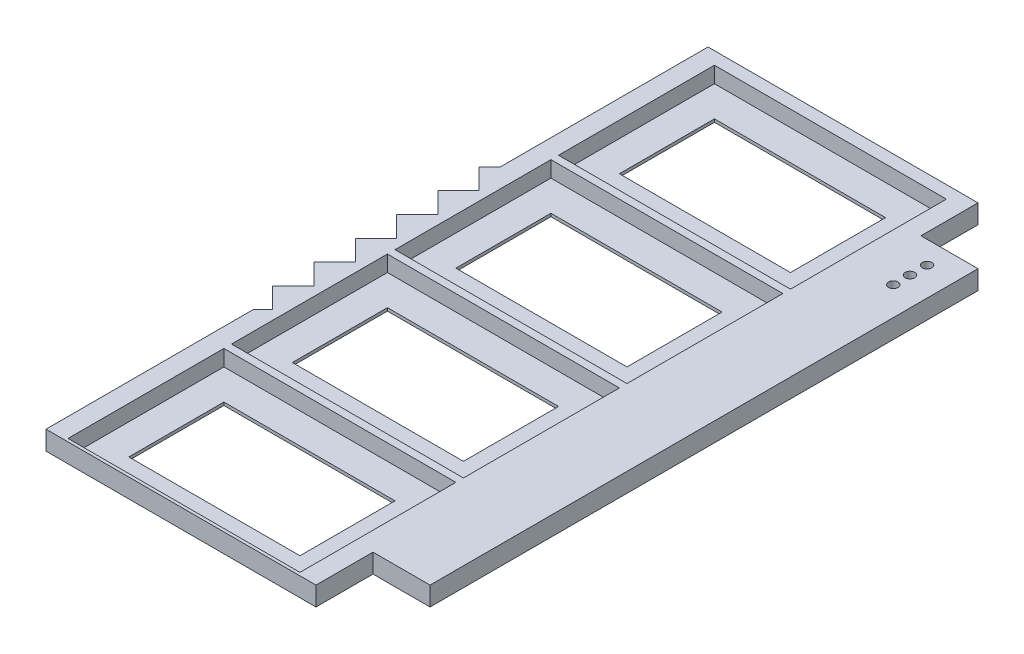
SolidWorks part; units mm, degrees
ref_plane "Front Plane" through (0, 0, 0) normal (0, 0, 1) x (1, 0, 0)
ref_plane "Top Plane" through (0, 0, 0) normal (0, 1, 0) x (1, 0, 0)
ref_plane "Right Plane" through (0, 0, 0) normal (1, 0, 0) x (0, 0, -1)
sketch "Sketch1" plane through (0, 0, 0) normal (0, 1, 0) x (1, 0, 0)
  line L0 (139.065, 94.1103) -> (139.065, -88.9) construction
  line L1 (-148.59, -107.95) -> (148.59, -107.95)
  line L2 (148.59, -107.95) -> (123.19, -107.95)
  line L3 (-156.21, 113.1603) -> (-137.0297, 113.1603)
  line L4 (148.59, -107.95) -> (148.59, 107.95)
  line L7 (148.59, -107.95) -> (-156.21, -107.95)
  line L8 (148.59, -107.95) -> (148.59, 113.1603)
  line L9 (148.59, 113.1603) -> (-156.21, 113.1603)
  line L10 (-156.21, -107.95) -> (-156.21, 113.1603)
  line L11 (-156.21, -107.95) -> (148.59, -107.95)
  line L12 (-156.21, -107.95) -> (-156.21, -106.95)
  line L13 (-156.21, -106.95) -> (148.59, -106.95)
  line L14 (148.59, -107.95) -> (148.59, -106.95)
  line L15 (148.59, -107.95) -> (148.59, 113.1603)
  line L16 (148.59, 113.1603) -> (123.19, 113.1603)
  line L17 (123.19, -107.95) -> (123.19, 113.1603)
  line L18 (123.19, -106.95) -> (45.72, -106.95)
  line L19 (123.19, -106.95) -> (123.19, -54.88)
  line L20 (123.19, -54.88) -> (45.72, -54.88)
  line L21 (45.72, -106.95) -> (45.72, -54.88)
  line L22 (123.19, -52.34) -> (45.72, -52.34)
  line L23 (123.19, -52.34) -> (123.19, -0.27)
  line L24 (123.19, -0.27) -> (45.72, -0.27)
  line L25 (45.72, -52.34) -> (45.72, -0.27)
  line L26 (123.19, 2.27) -> (45.72, 2.27)
  line L27 (123.19, 2.27) -> (123.19, 54.34)
  line L28 (123.19, 54.34) -> (45.72, 54.34)
  line L29 (45.72, 2.27) -> (45.72, 54.34)
  line L30 (123.19, 56.88) -> (45.72, 56.88)
  line L31 (123.19, 56.88) -> (123.19, 108.95)
  line L32 (123.19, 108.95) -> (45.72, 108.95)
  line L33 (45.72, 56.88) -> (45.72, 108.95)
  line L34 (33.02, -52.34) -> (-44.45, -52.34)
  line L35 (33.02, -106.95) -> (-44.45, -106.95)
  line L36 (33.02, -106.95) -> (33.02, -54.88)
  line L37 (33.02, -54.88) -> (-44.45, -54.88)
  line L38 (-44.45, -106.95) -> (-44.45, -54.88)
  line L39 (-57.15, -106.95) -> (-134.62, -106.95)
  line L40 (-57.15, -106.95) -> (-57.15, -54.88)
  line L41 (-57.15, -54.88) -> (-134.62, -54.88)
  line L42 (-134.62, -106.95) -> (-134.62, -54.88)
  line L43 (33.02, -52.34) -> (33.02, 0)
  line L44 (33.02, 0) -> (-44.45, 0)
  line L45 (-44.45, -52.34) -> (-44.45, 0)
  line L46 (-57.15, -52.34) -> (-134.62, -52.34)
  line L47 (-57.15, -52.34) -> (-57.15, -0.27)
  line L48 (-57.15, -0.27) -> (-134.62, -0.27)
  line L49 (-134.62, -52.34) -> (-134.62, -0.27)
  line L50 (33.02, 2.27) -> (-44.45, 2.27)
  line L51 (33.02, 2.27) -> (33.02, 54.34)
  line L52 (33.02, 54.34) -> (-44.45, 54.34)
  line L53 (-44.45, 2.27) -> (-44.45, 54.34)
  line L54 (-57.15, 2.27) -> (-134.62, 2.27)
  line L55 (-57.15, 2.27) -> (-57.15, 54.34)
  line L56 (-57.15, 54.34) -> (-134.62, 54.34)
  line L57 (-134.62, 2.27) -> (-134.62, 54.34)
  line L58 (33.02, 56.88) -> (-44.45, 56.88)
  line L59 (33.02, 56.88) -> (33.02, 108.95)
  line L60 (33.02, 108.95) -> (-44.45, 108.95)
  line L61 (-44.45, 56.88) -> (-44.45, 108.95)
  line L62 (-57.15, 56.88) -> (-134.62, 56.88)
  line L63 (-57.15, 56.88) -> (-57.15, 108.95)
  line L64 (-57.15, 108.95) -> (-134.62, 108.95)
  line L65 (-134.62, 56.88) -> (-134.62, 108.95)
  line L66 (-156.21, 113.1603) -> (-156.21, 100.4603)
  line L67 (-156.21, 113.1603) -> (-156.21, 93.98)
  line L68 (-156.21, 93.98) -> (-137.0297, 93.98)
  line L69 (-156.21, -107.95) -> (-137.16, -107.95)
  line L70 (-156.21, -107.95) -> (-156.21, -88.9)
  line L71 (-156.21, -88.9) -> (-137.16, -88.9)
  line L72 (-137.16, -107.95) -> (-137.16, -88.9)
  line L73 (-137.0297, 113.1603) -> (-137.0297, 93.98)
  line L74 (148.59, 113.1603) -> (129.54, 113.1603)
  line L75 (148.59, 113.1603) -> (148.59, 94.1103)
  line L76 (148.59, 94.1103) -> (129.54, 94.1103)
  line L77 (129.54, 113.1603) -> (129.54, 94.1103)
  line L78 (148.59, -107.95) -> (129.54, -107.95)
  line L79 (148.59, -107.95) -> (148.59, -88.9)
  line L80 (148.59, -88.9) -> (129.54, -88.9)
  line L81 (129.54, -107.95) -> (129.54, -88.9)
  circle A0 centre (139.065, 86.619) radius 1.5875
  circle A1 centre (139.065, 80.9106) radius 1.5875
  circle A2 centre (139.065, 75.3349) radius 1.5875
  point P0 (0, 0)
  point P3 (-137.16, -106.95)
  point P15 (123.19, -106.95)
  point P78 (-137.16, -107.95)
  point P79 (-156.21, -106.95)
  dimension "D1" = 215.9
  dimension "D2" = 297.18
  dimension "D3" = 1
  dimension "D4" = 25.4
  dimension "D5" = 2.54
  dimension "D6" = 2.54
  dimension "D7" = 2.54
  dimension "D8" = 12.7
  dimension "D9" = 12.7
extrude "Boss-Extrude3" add sketch "Sketch1" along normal blind 6.35 contours L76 L0 A0 A1 A2 L80 L15 | L0 L76 L77 L16 L17 L13 L81 L80 A2 A1 A0 | L9 L73 L68 L10 L71 L72 L13 L42 L41 L40 L38 L37 L36 L21 L20 L17 L22 L25 L24 L26 L29 L28 L30 L33 L32 L62 L65 L64 L63 L54 L57 L56 L55 L46 L49 L48 L47 L34 L45 L44 L43
sketch "Sketch2" plane through (0, 6.35, 0) normal (0, 1, 0) x (1, 0, 0)
  line L0 (148.59, -107.95) -> (148.59, -106.95) construction
  line L1 (129.54, -106.95) -> (148.59, -106.95)
  line L2 (129.54, -106.95) -> (129.54, -107.95)
  line L3 (129.54, -107.95) -> (148.59, -107.95)
  line L4 (148.59, -106.95) -> (148.59, -107.95)
  line L5 (-156.21, -107.95) -> (148.59, -107.95) construction
extrude "Cut-Extrude1" cut sketch "Sketch2" against normal through all
ref_plane "Plane1" through (-137.16, 6.35, 106.95) normal (0, -1, 0) x (-1, 0, 0)
sketch "Sketch4" plane through (0, 6.35, 0) normal (0, 1, 0) x (1, 0, 0)
  line L1 (-156.21, -107.95) -> (-137.16, -107.95)
  line L2 (-156.21, -107.95) -> (-156.21, -106.95)
  line L3 (-156.21, -106.95) -> (-137.16, -106.95)
  line L4 (-137.16, -107.95) -> (-137.16, -106.95)
extrude "Cut-Extrude2" cut sketch "Sketch4" against normal through all
sketch "Sketch5" plane through (0, 0, -108.95) normal (0, 0, 1) x (1, 0, 0)
  line L1 (-134.62, 6.35) -> (-134.62, 0) construction
  line L2 (123.19, 0) -> (-134.62, 0)
  line L3 (123.19, 0) -> (123.19, 1)
  line L4 (123.19, 1) -> (-134.62, 1)
  line L5 (-134.62, 0) -> (-134.62, 1)
extrude "Boss-Extrude4" add sketch "Sketch5" along normal through all
sketch "Sketch6" plane through (0, 1, 0) normal (0, 1, 0) x (1, 0, 0)
  line L0 (-134.62, 2.27) -> (-57.15, 54.34) construction
  line L1 (-134.62, 108.95) -> (-57.15, 56.88) construction
  line L2 (-57.15, 108.95) -> (-134.62, 56.88) construction
  line L3 (-124.46, 67.04) -> (-67.31, 67.04)
  line L4 (-124.46, 67.04) -> (-124.46, 98.79)
  line L5 (-124.46, 98.79) -> (-67.31, 98.79)
  line L6 (-67.31, 67.04) -> (-67.31, 98.79)
  line L7 (-124.46, 67.04) -> (-67.31, 98.79) construction
  line L8 (-124.46, 98.79) -> (-67.31, 67.04) construction
  line L9 (-134.62, 2.27) -> (-57.15, 2.27) construction
  line L10 (-134.62, 54.34) -> (-57.15, 54.34) construction
  line L11 (-57.15, 54.34) -> (-57.15, 2.27) construction
  line L12 (-134.62, 54.34) -> (-57.15, 2.27) construction
  line L13 (-57.15, -0.27) -> (-134.62, -52.34) construction
  line L14 (-124.46, 44.18) -> (-67.31, 44.18)
  line L15 (-124.46, 44.18) -> (-124.46, 12.43)
  line L16 (-124.46, 12.43) -> (-67.31, 12.43)
  line L17 (-67.31, 44.18) -> (-67.31, 12.43)
  line L18 (-124.46, 44.18) -> (-67.31, 12.43) construction
  line L19 (-124.46, 12.43) -> (-67.31, 44.18) construction
  line L20 (-134.62, -0.27) -> (-57.15, -52.34) construction
  line L21 (-57.15, -0.27) -> (-57.15, -52.34) construction
  line L22 (-57.15, -54.88) -> (-134.62, -106.95) construction
  line L23 (-124.46, -10.43) -> (-67.31, -10.43)
  line L24 (-124.46, -10.43) -> (-124.46, -42.18)
  line L25 (-124.46, -42.18) -> (-67.31, -42.18)
  line L26 (-67.31, -10.43) -> (-67.31, -42.18)
  line L27 (-124.46, -10.43) -> (-67.31, -42.18) construction
  line L28 (-124.46, -42.18) -> (-67.31, -10.43) construction
  line L29 (-134.62, -54.88) -> (-57.15, -54.88) construction
  line L30 (-134.62, -54.88) -> (-57.15, -106.95) construction
  line L31 (33.02, 108.95) -> (-44.45, 56.88) construction
  line L32 (-124.46, -65.04) -> (-67.31, -65.04)
  line L33 (-124.46, -65.04) -> (-124.46, -96.79)
  line L34 (-124.46, -96.79) -> (-67.31, -96.79)
  line L35 (-67.31, -65.04) -> (-67.31, -96.79)
  line L36 (-124.46, -65.04) -> (-67.31, -96.79) construction
  line L37 (-124.46, -96.79) -> (-67.31, -65.04) construction
  line L38 (33.02, 108.95) -> (33.02, 56.88) construction
  line L39 (33.02, 108.95) -> (-44.45, 108.95) construction
  line L40 (33.02, 56.88) -> (-44.45, 108.95) construction
  line L41 (-44.45, 56.88) -> (33.02, 56.88) construction
  line L42 (123.19, 108.95) -> (45.72, 56.88) construction
  line L43 (-34.29, 67.04) -> (22.86, 67.04)
  line L44 (-34.29, 67.04) -> (-34.29, 98.79)
  line L45 (-34.29, 98.79) -> (22.86, 98.79)
  line L46 (22.86, 67.04) -> (22.86, 98.79)
  line L47 (-34.29, 67.04) -> (22.86, 98.79) construction
  line L48 (-34.29, 98.79) -> (22.86, 67.04) construction
  line L49 (45.72, 108.95) -> (123.19, 56.88) construction
  line L51 (55.88, 98.79) -> (113.03, 98.79)
  line L52 (55.88, 98.79) -> (55.88, 67.04)
  line L53 (55.88, 67.04) -> (113.03, 67.04)
  line L54 (113.03, 98.79) -> (113.03, 67.04)
  line L55 (55.88, 98.79) -> (113.03, 67.04) construction
  line L56 (55.88, 67.04) -> (113.03, 98.79) construction
  line L57 (-34.29, 12.43) -> (22.86, 12.43)
  line L58 (-34.29, 12.43) -> (-34.29, 44.18)
  line L59 (-34.29, 44.18) -> (22.86, 44.18)
  line L60 (22.86, 12.43) -> (22.86, 44.18)
  line L61 (-34.29, 12.43) -> (22.86, 44.18) construction
  line L62 (-34.29, 44.18) -> (22.86, 12.43) construction
  line L63 (-34.29, -42.18) -> (22.86, -42.18)
  line L64 (-34.29, -42.18) -> (-34.29, -10.43)
  line L65 (-34.29, -10.43) -> (22.86, -10.43)
  line L66 (22.86, -42.18) -> (22.86, -10.43)
  line L67 (-34.29, -42.18) -> (22.86, -10.43) construction
  line L68 (-34.29, -10.43) -> (22.86, -42.18) construction
  line L69 (-34.29, -96.79) -> (22.86, -96.79)
  line L70 (-34.29, -96.79) -> (-34.29, -65.04)
  line L71 (-34.29, -65.04) -> (22.86, -65.04)
  line L72 (22.86, -96.79) -> (22.86, -65.04)
  line L73 (-34.29, -96.79) -> (22.86, -65.04) construction
  line L74 (-34.29, -65.04) -> (22.86, -96.79) construction
  line L75 (55.88, -96.79) -> (113.03, -96.79)
  line L76 (55.88, -96.79) -> (55.88, -65.04)
  line L77 (55.88, -65.04) -> (113.03, -65.04)
  line L78 (113.03, -96.79) -> (113.03, -65.04)
  line L79 (55.88, -96.79) -> (113.03, -65.04) construction
  line L80 (55.88, -65.04) -> (113.03, -96.79) construction
  line L81 (55.88, -42.18) -> (113.03, -42.18)
  line L82 (55.88, -42.18) -> (55.88, -10.43)
  line L83 (55.88, -10.43) -> (113.03, -10.43)
  line L84 (113.03, -42.18) -> (113.03, -10.43)
  line L85 (55.88, -42.18) -> (113.03, -10.43) construction
  line L86 (55.88, -10.43) -> (113.03, -42.18) construction
  line L87 (55.88, 12.43) -> (113.03, 12.43)
  line L88 (55.88, 12.43) -> (55.88, 44.18)
  line L89 (55.88, 44.18) -> (113.03, 44.18)
  line L90 (113.03, 12.43) -> (113.03, 44.18)
  line L91 (55.88, 12.43) -> (113.03, 44.18) construction
  line L92 (55.88, 44.18) -> (113.03, 12.43) construction
  point P4 (-95.885, 82.915)
  point P23 (-95.885, 28.305)
  point P37 (-95.885, -26.305)
  point P51 (-95.885, -80.915)
  point P68 (-5.715, 82.915)
  point P81 (84.455, 82.915)
  point P86 (-5.715, 28.305)
  point P91 (-5.715, -26.305)
  point P96 (-5.715, -80.915)
  point P101 (84.455, -80.915)
  point P106 (84.455, -26.305)
  point P111 (84.455, 28.305)
extrude "Cut-Extrude3" cut sketch "Sketch6" against normal through all
sketch "Sketch7" plane through (0, 6.35, 0) normal (0, 1, 0) x (1, 0, 0)
  line L0 (39.37, 43.8468) -> (35.7888, 40.2655)
  line L2 (39.37, -107.95) -> (-160.9513, -107.95)
  line L3 (39.37, 43.8468) -> (39.37, 113.1603)
  line L5 (39.37, 113.1603) -> (-160.9513, 113.1603)
  line L6 (35.7888, 40.2655) -> (42.6794, 33.3749)
  line L7 (42.6794, 33.3749) -> (35.7888, 26.4843)
  line L8 (35.7888, 26.4843) -> (42.6794, 19.5937)
  line L9 (42.6794, 19.5937) -> (39.37, 16.2843)
  line L10 (129.54, 113.1603) -> (-137.0297, 113.1603) construction
  line L11 (39.37, -38.8407) -> (39.37, -107.95)
  line L12 (-160.9513, -107.95) -> (-160.9513, 113.1603)
  line L13 (39.37, 16.2843) -> (35.7888, 12.7031)
  line L14 (35.7888, 12.7031) -> (42.6794, 5.8124)
  line L15 (42.6794, 5.8124) -> (35.7888, -1.0782)
  line L16 (35.7888, -1.0782) -> (42.6794, -7.9688)
  line L17 (42.6794, -7.9688) -> (35.7888, -14.8594)
  line L18 (35.7888, -14.8594) -> (39.37, -18.4406)
  line L19 (39.37, -18.4406) -> (42.6794, -21.75)
  line L20 (42.6794, -21.75) -> (35.7888, -28.6407)
  line L21 (35.7888, -28.6407) -> (42.6794, -35.5313)
  line L22 (42.6794, -35.5313) -> (39.37, -38.8407)
  line L23 (-137.16, -107.95) -> (129.54, -107.95) construction
extrude "Cut-Extrude5" cut sketch "Sketch7" against normal through all
